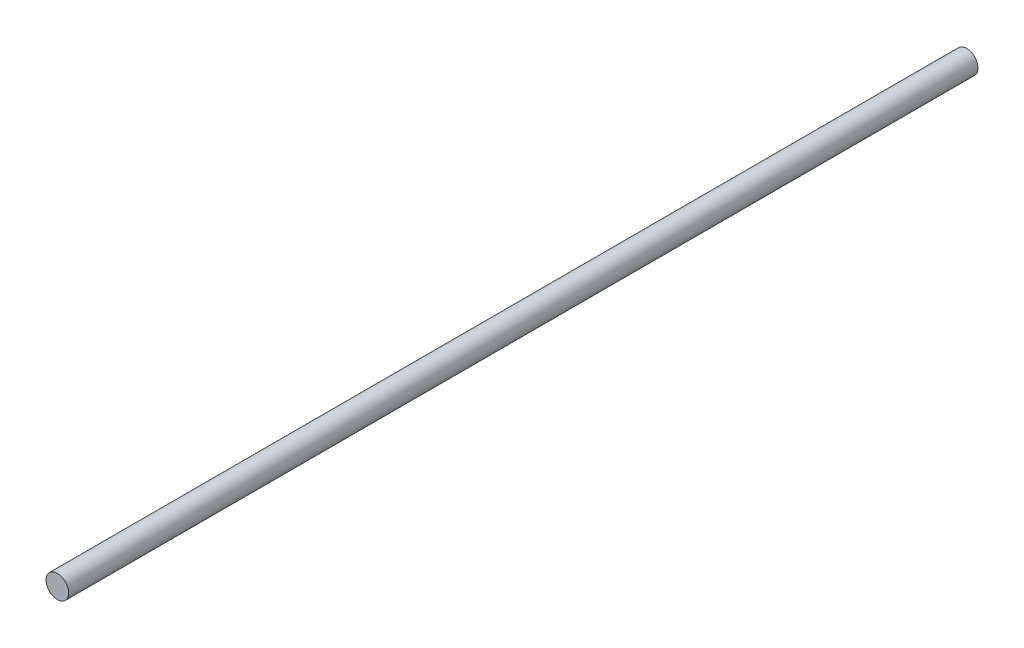
SolidWorks part; units mm, degrees
ref_plane "Front Plane" through (0, 0, 0) normal (0, 0, 1) x (1, 0, 0)
ref_plane "Top Plane" through (0, 0, 0) normal (0, 1, 0) x (1, 0, 0)
ref_plane "Right Plane" through (0, 0, 0) normal (1, 0, 0) x (0, 0, -1)
sketch "Sketch1" plane through (0, 0, 0) normal (0, 0, 1) x (1, 0, 0)
  circle A0 centre (0, 0) radius 1
  dimension "D1" = 2
extrude "Boss-Extrude1" add sketch "Sketch1" along normal blind 80
